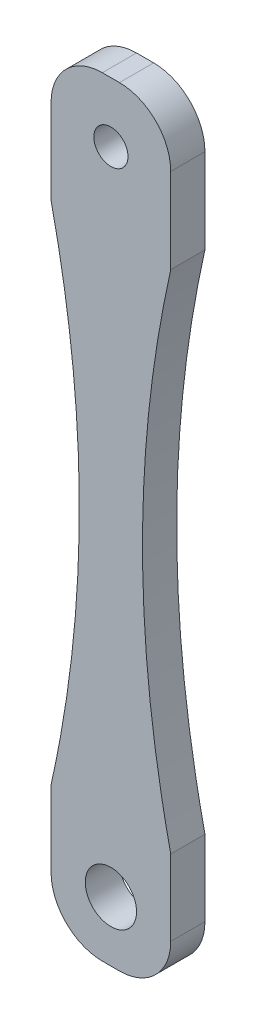
SolidWorks part; units mm, degrees
ref_plane "Front Plane" through (0, 0, 0) normal (0, 0, 1) x (1, 0, 0)
ref_plane "Top Plane" through (0, 0, 0) normal (0, 1, 0) x (1, 0, 0)
ref_plane "Right Plane" through (0, 0, 0) normal (1, 0, 0) x (0, 0, -1)
sketch "Sketch1" plane through (0, 0, 0) normal (0, 0, 1) x (1, 0, 0)
  line L1 (-0.5, 22.5) -> (0.5, 22.5)
  line L2 (-3.5, 19.5) -> (-3.5, -19.5)
  line L3 (-0.5, -22.5) -> (0.5, -22.5)
  line L4 (3.5, 19.5) -> (3.5, -19.5)
  line L5 (-3.5, 22.5) -> (3.5, -22.5) construction
  line L6 (-3.5, -22.5) -> (3.5, 22.5) construction
  arc A0 (-3.5, -19.5) -> (-0.5, -22.5) centre (-0.5, -19.5) ccw
  arc A1 (0.5, -22.5) -> (3.5, -19.5) centre (0.5, -19.5) ccw
  arc A2 (0.5, 22.5) -> (3.5, 19.5) centre (0.5, 19.5) cw
  arc A3 (-0.5, 22.5) -> (-3.5, 19.5) centre (-0.5, 19.5) ccw
  circle A4 centre (0, 19) radius 1
  circle A5 centre (0, -19) radius 1.5
  point P0 (0, 0)
  point P24 (-0.0518, -22.5)
  point P25 (-0.1285, 22.5)
  dimension "D3" = 3
  dimension "D4" = 2
  dimension "D5" = 3
  dimension "D1" = 7
  dimension "D2" = 45
  dimension "D6" = 3.5
  dimension "D7" = 3.5
  dimension "D8" = 3.5
  dimension "D9" = 3.5
extrude "Boss-Extrude1" add sketch "Sketch1" along normal blind 2
sketch "Sketch2" plane through (0, 0, 2) normal (0, 0, 1) x (1, 0, 0)
  line L0 (-3.5, 19.5) -> (-3.5, -19.5) construction
  line L1 (0, 0) -> (0, -6.8177) construction
  line L6 (-0.5, -22.5) -> (0.5, -22.5)
  line L7 (3.5, -19.5) -> (3.5, 19.5)
  line L8 (0.5, 22.5) -> (-0.5, 22.5)
  line L9 (-3.5, 19.5) -> (-3.5, -19.5)
  line L10 (-0.5, -22.5) -> (0.5, -22.5)
  line L11 (3.5, -19.5) -> (3.5, 19.5)
  line L12 (0.5, 22.5) -> (-0.5, 22.5)
  line L13 (-3.5, 19.5) -> (-3.5, -19.5)
  arc A4 (-3.5, -19.5) -> (-0.5, -22.5) centre (-0.5, -19.5) ccw
  arc A5 (0.5, -22.5) -> (3.5, -19.5) centre (0.5, -19.5) ccw
  arc A6 (3.5, 19.5) -> (0.5, 22.5) centre (0.5, 19.5) ccw
  arc A7 (-0.5, 22.5) -> (-3.5, 19.5) centre (-0.5, 19.5) ccw
  arc A8 (-3.5, -19.5) -> (-0.5, -22.5) centre (-0.5, -19.5) ccw
  arc A9 (0.5, -22.5) -> (3.5, -19.5) centre (0.5, -19.5) ccw
  arc A10 (3.5, 19.5) -> (0.5, 22.5) centre (0.5, 19.5) ccw
  arc A11 (-0.5, 22.5) -> (-3.5, 19.5) centre (-0.5, 19.5) ccw
  spline S0 degree 2 poles (-3.5, 14.5305) (-0.195, -0.2631) (-3.5, -15.0699) knots 0 0 0 1 1 1
  spline S1 degree 2 poles (3.5, 14.5305) (0.195, -0.2631) (3.5, -15.0699) knots 0 0 0 1 1 1
  dimension "D1" = 0
extrude "Cut-Extrude1" cut sketch "Sketch2" against normal blind 14 contours S0 L13 | L11 S1
